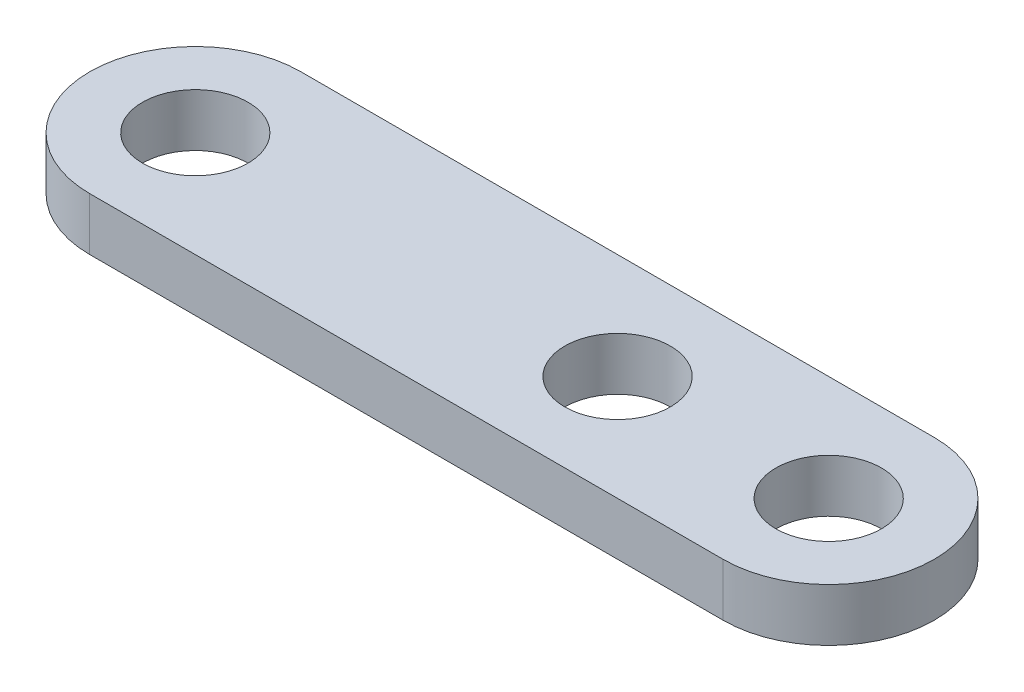
SolidWorks part; units mm, degrees
ref_plane "Front Plane" through (0, 0, 0) normal (0, 0, 1) x (1, 0, 0)
ref_plane "Top Plane" through (0, 0, 0) normal (0, 1, 0) x (1, 0, 0)
ref_plane "Right Plane" through (0, 0, 0) normal (1, 0, 0) x (0, 0, -1)
sketch "Sketch1" plane through (0, 0, 0) normal (0, 1, 0) x (1, 0, 0)
  line L0 (-72.3468, 0) -> (-12.3468, 0) construction
  line L1 (-72.3468, 10) -> (-12.3468, 10)
  line L2 (-72.3468, -10) -> (-12.3468, -10)
  arc A0 (-72.3468, 10) -> (-72.3468, -10) centre (-72.3468, 0) ccw
  arc A1 (-12.3468, -10) -> (-12.3468, 10) centre (-12.3468, 0) ccw
  circle A2 centre (-72.3468, 0) radius 5
  circle A3 centre (-12.3468, 0) radius 5
  point P3 (-42.3468, 0)
  dimension "D1" = 60
  dimension "D2" = 10
  dimension "D3" = 10
  dimension "D4" = 10
extrude "Boss-Extrude1" add sketch "Sketch1" along normal blind 5
sketch "Sketch2" plane through (0, 5, 0) normal (0, 1, 0) x (1, 0, 0)
  circle A0 centre (-32.3468, 0) radius 5
  arc A1 (-12.3468, -10) -> (-12.3468, 10) centre (-12.3468, 0) ccw construction
  dimension "D1" = 10
  dimension "D2" = 20
extrude "Cut-Extrude1" cut sketch "Sketch2" against normal blind 10
